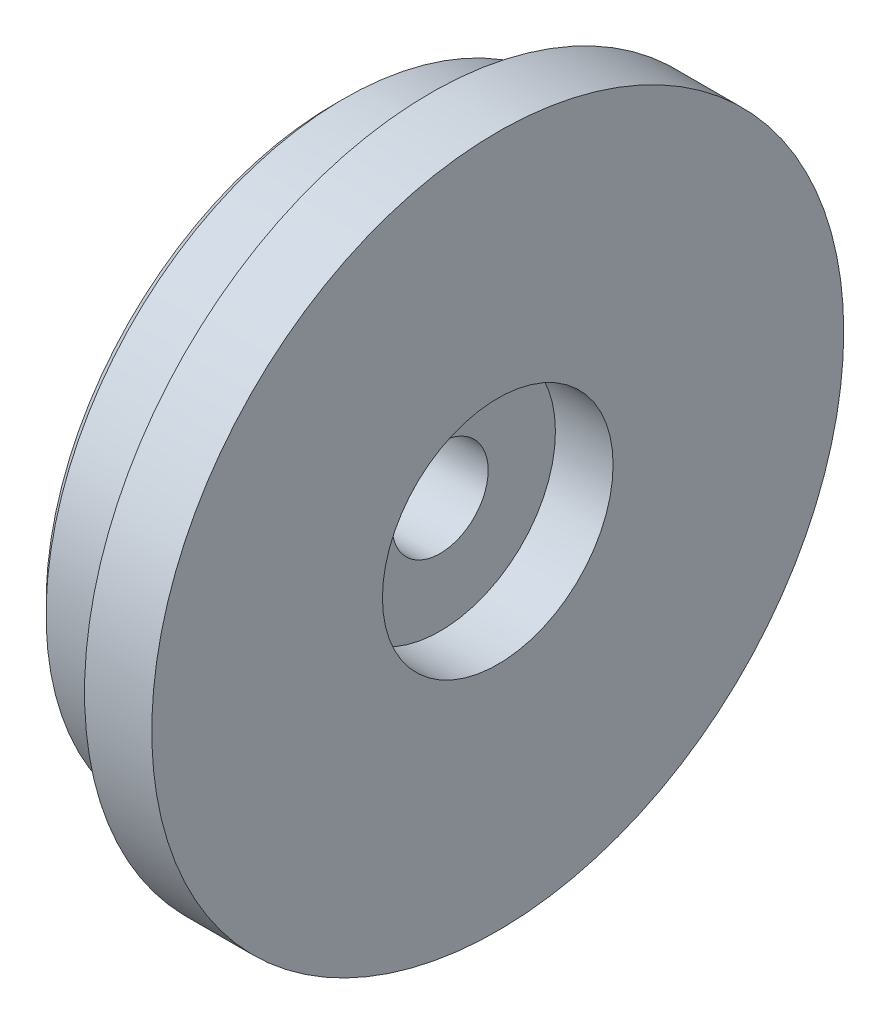
SolidWorks part; units mm, degrees
material "Alliage de zinc AC41A, brut"
ref_plane "Plan de face" through (0, 0, 0) normal (0, 0, 1) x (1, 0, 0)
ref_plane "Plan de dessus" through (0, 0, 0) normal (0, 1, 0) x (1, 0, 0)
ref_plane "Plan de droite" through (0, 0, 0) normal (1, 0, 0) x (0, 0, -1)
sketch "Esquisse1" plane through (0, 0, 0) normal (0, 0, 1) x (1, 0, 0)
  line L1 (0, 18) -> (-3.5, 18)
  line L2 (0, 18) -> (0, 6)
  line L3 (-3.5, 18) -> (-3.5, 15)
  line L4 (-3.5, 15) -> (-4.5, 15)
  line L5 (-4.5, 15) -> (-4.5, 15.5)
  line L6 (-4.5, 15.5) -> (-8, 15.5)
  line L8 (0, 6) -> (-3, 6)
  line L9 (-3, 6) -> (-3, 2.5)
  line L10 (-3, 2.5) -> (-8.5, 2.5)
  line L11 (-8, 15.5) -> (-8.5, 15)
  line L12 (-8.5, 2.5) -> (-8.5, 5)
  line L13 (-8.5, 5) -> (-5.75, 5)
  line L14 (-5, 5.75) -> (-5, 11.25)
  line L15 (-5.75, 12) -> (-8.5, 12)
  line L16 (-8.5, 12) -> (-8.5, 15)
  line L17 (-5, 11.25) -> (-5.75, 12)
  line L18 (-5.75, 5) -> (-5, 5.75)
  line L19 (0, 0) -> (-8.5, 0) construction
  line L20 (0, 0) -> (0, 6) construction
  point P13 (-5, 5)
  point P15 (-5, 12)
  point P22 (0, 0)
  point P23 (0, 0)
  dimension "D2" = 3.5
  dimension "D3" = 12
  dimension "D4" = 3
  dimension "D5" = 1
  dimension "D6" = 0.5
  dimension "D7" = 2.75
  dimension "D8" = 2.5
  dimension "D9" = 3
  dimension "D10" = 3.5
  dimension "D11" = 5.5
  dimension "D12" = 3.5
  dimension "D19" = 18
  dimension "D13" = 0.5
  dimension "D14" = 7
  dimension "D15" = 3
  dimension "D17" = 0.75
  dimension "D20" = 0.75
  dimension "D18" = 0.75
  dimension "D16" = 3.5
  dimension "D21" = 0.75
  dimension "D22" = 6
revolve "Révolution1789" add sketch "Esquisse1" angle 360 about L19
cosmetic thread "Représentation de filetage1" parameters "D2"=30
cosmetic thread "Représentation de filetage2" parameters "D2"=6
